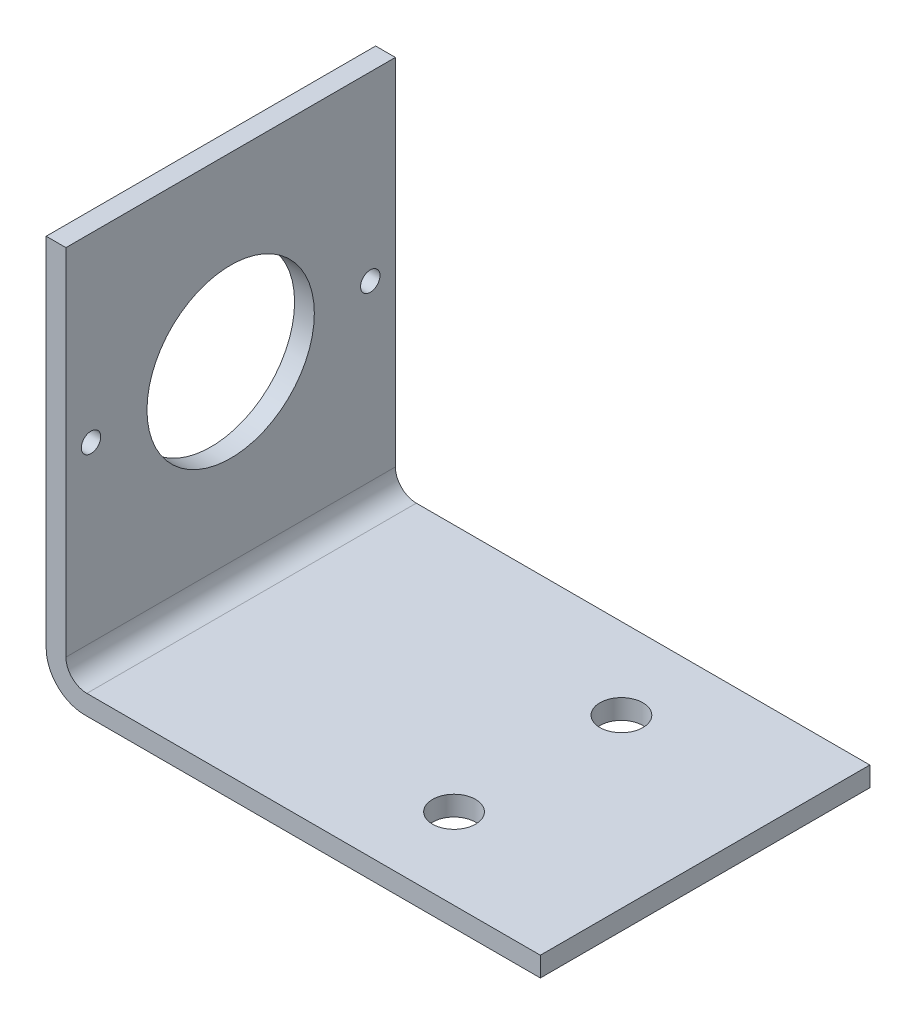
SolidWorks part; units mm, degrees
ref_plane "Front" through (0, 0, 0) normal (0, 0, 1) x (1, 0, 0)
ref_plane "Top" through (0, 0, 0) normal (0, 1, 0) x (1, 0, 0)
ref_plane "Right" through (0, 0, 0) normal (1, 0, 0) x (0, 0, -1)
sketch "Sketch2" plane through (0, 0, 0) normal (0, 0, 1) x (1, 0, 0)
  line L0 (0, 5.842) -> (0, 59.9948)
  line L1 (5.842, 0) -> (75, 0)
  line L2 (6.1722, 2.9972) -> (75, 2.9972)
  line L3 (2.9972, 6.1722) -> (2.9972, 59.9948)
  line L4 (0, 59.9948) -> (2.9972, 59.9948)
  line L5 (75, 2.9972) -> (75, 0)
  line L6 (2.9972, 2.9972) -> (75, 2.9972) construction
  line L7 (2.9972, 2.9972) -> (2.9972, 59.9948) construction
  line L8 (0, 0) -> (0, 59.9948) construction
  line L9 (0, 0) -> (75, 0) construction
  arc A0 (6.1722, 2.9972) -> (2.9972, 6.1722) centre (6.1722, 6.1722) cw
  arc A1 (0, 5.842) -> (5.842, 0) centre (5.842, 5.842) ccw
  point P13 (0, 0)
  dimension "D4" = 3.175
  dimension "D5" = 5.842
  dimension "D2" = 75
  dimension "D3" = 59.9948
  dimension "D1" = 2.9972
extrude "Boss-Extrude1" add sketch "Sketch2" along normal blind 50
sketch "Sketch3" plane through (0, 0, 0) normal (-1, 0, 0) x (0, 0, 1)
  line L0 (50, 0) -> (0, 0) construction
  line L1 (50, 35.5) -> (0, 35.5) construction
  line L2 (50, 59.9948) -> (50, 5.842) construction
  line L3 (0, 59.9948) -> (0, 5.842) construction
  circle A0 centre (25, 35.5) radius 12.7
  circle A2 centre (25, 35.5) radius 16.6688 construction
  point P5 (25, 35.5)
  dimension "D1" = 25.4
  dimension "D5" = 33.3375
  dimension "D2" = 35.5
extrude "Bearing -- Without motor" [suppressed] cut sketch "Sketch3" against normal through all
sketch "Sketch4" [suppressed] plane through (0, 0, 0) normal (-1, 0, 0) x (0, 0, 1)
  line L0 (0, 59.9948) -> (0, 5.842) construction
  line L1 (25, 35.5) -> (25, 41.6125) construction
  circle A0 centre (3.81, 35.5) radius 1.4732
  circle A2 centre (46.19, 35.5) radius 1.4732
  point P6 (25, 35.5)
  dimension "D1" = 2.9464
  dimension "D2" = 3.81
extrude "4-40 -- Without Motor" [suppressed] cut sketch "Sketch4" against normal through all
sketch "Sketch5" plane through (0, 2.9972, 0) normal (0, 1, 0) x (1, 0, 0)
  line L0 (75, -50) -> (75, 0) construction
  line L1 (49.6, -12.3) -> (49.6, -37.7) construction
  circle A0 centre (49.6, -12.3) radius 3.2639
  circle A1 centre (49.6, -37.7) radius 3.2639
  point P4 (49.6, -25)
  point P7 (75, -25)
  dimension "D1" = 6.5278
  dimension "D2" = 25.4
  dimension "D3" = 25.4
extrude "Mounting -- Horizontal" cut sketch "Sketch5" against normal through all
sketch "Sketch7" plane through (0, 0, 0) normal (-1, 0, 0) x (0, 0, 1)
  line L0 (0, 32.5) -> (50, 32.5) construction
  line L1 (0, 59.9948) -> (0, 5.842) construction
  line L2 (50, 59.9948) -> (50, 5.842) construction
  circle A0 centre (25, 32.5) radius 12.7
  dimension "D1" = 32.5
  dimension "D2" = 25.4
extrude "Bearing -- With Motor" cut sketch "Sketch7" against normal through all
sketch "Sketch8" plane through (0, 0, 0) normal (-1, 0, 0) x (0, 0, 1)
  line L0 (0, 59.9948) -> (0, 5.842) construction
  line L1 (25, 32.5) -> (25, 41.7881) construction
  circle A0 centre (3.81, 32.5) radius 1.4732
  circle A1 centre (46.19, 32.5) radius 1.4732
  point P4 (25, 32.5)
  dimension "D1" = 2.9464
  dimension "D2" = 3.81
extrude "4-40 -- With Motor" cut sketch "Sketch8" against normal through all
sketch "Sketch9" [suppressed] plane through (0, 2.9972, 0) normal (0, 1, 0) x (1, 0, 0)
  line L0 (26.74, -15.1) -> (26.74, -34.9) construction
  line L1 (75, -50) -> (75, 0) construction
  circle A0 centre (26.74, -15.1) radius 3.3
  circle A1 centre (26.74, -34.9) radius 3.3
  point P8 (26.74, -25)
  point P9 (75, -25)
  dimension "D1" = 6.6
  dimension "D3" = 19.8
  dimension "D4" = 48.26
extrude "Mounting -- Vertical Without Motor" [suppressed] cut sketch "Sketch9" against normal through all
sketch "Sketch10" [suppressed] plane through (0, 2.9972, 0) normal (0, 1, 0) x (1, 0, 0)
  line L0 (36.9, -15.1) -> (36.9, -34.9) construction
  line L1 (75, -50) -> (75, 0) construction
  circle A0 centre (36.9, -15.1) radius 3.3
  circle A1 centre (36.9, -34.9) radius 3.3
  point P4 (36.9, -25)
  point P5 (75, -25)
  dimension "D1" = 6.6
  dimension "D2" = 19.8
  dimension "D3" = 38.1
extrude "Mounting -- Vertical With Motor" [suppressed] cut sketch "Sketch10" against normal through all
equation "\"D5@Sketch2\"=\"D4@Sketch2\"+.105"
